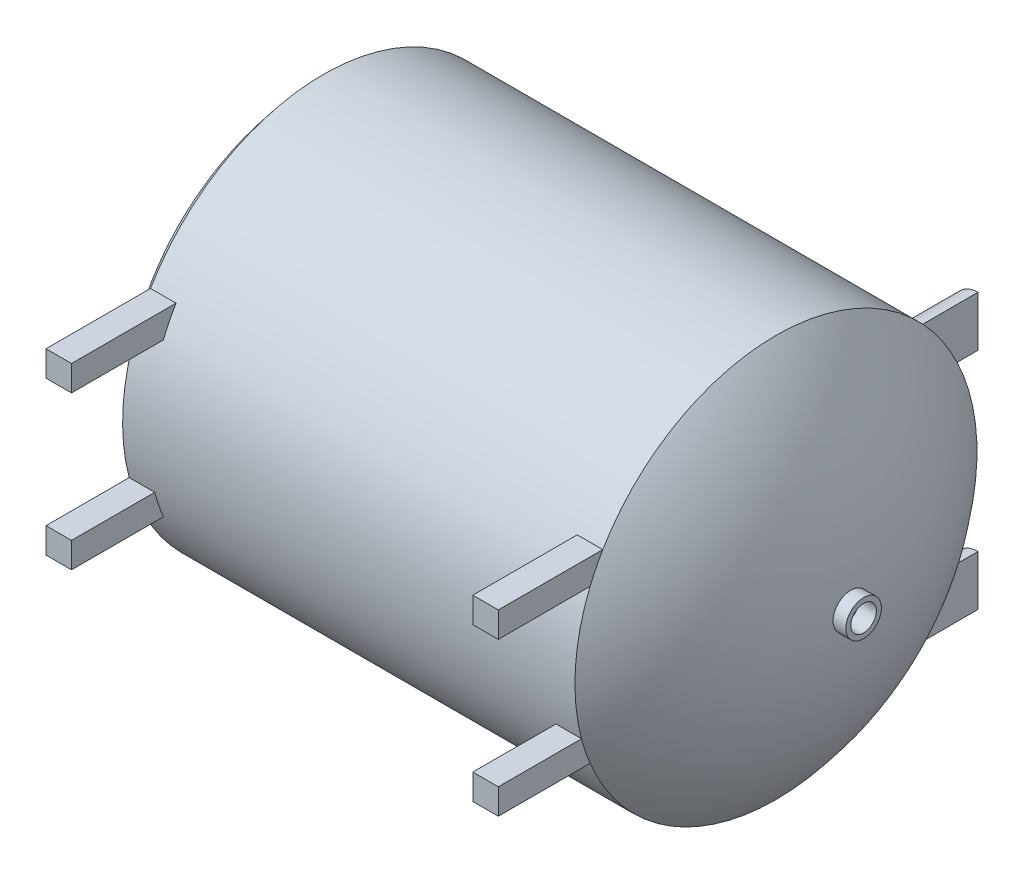
SolidWorks part; units mm, degrees
material "1060 Alloy"
ref_plane "Front" through (0, 0, 0) normal (0, 0, 1) x (1, 0, 0)
ref_plane "Top" through (0, 0, 0) normal (0, 1, 0) x (1, 0, 0)
ref_plane "Right" through (0, 0, 0) normal (1, 0, 0) x (0, 0, -1)
sketch "Sketch1" plane through (0, 0, 0) normal (0, 0, 1) x (1, 0, 0)
  line L0 (150, -400) -> (1050, -400)
  line L1 (600, -400) -> (600, 130.2021) construction
  line L2 (1198.9691, -35.4) -> (1224.3691, -35.4)
  line L3 (1224.3691, -35.4) -> (1224.3691, -25.4)
  line L4 (1224.3691, -25.4) -> (1199.4695, -25.4)
  line L5 (0, 0) -> (1200, 0) construction
  line L6 (154.5682, -390) -> (1045.4318, -390)
  line L7 (1199.4695, -25.4) -> (1189.4606, -25.4)
  line L8 (0, 0) -> (10, 0)
  arc A0 (0, 0) -> (150, -400) centre (608.3333, 0) ccw
  arc A1 (1198.9691, -35.4) -> (1050, -400) centre (591.6667, 0) cw
  arc A2 (1200, 0) -> (1199.4695, -25.4) centre (591.6667, 0) cw construction
  arc A3 (10, 0) -> (154.5682, -390) centre (608.3333, 0) ccw
  arc A4 (1189.4606, -25.4) -> (1045.4318, -390) centre (591.6667, 0) cw
  arc A6 (1189.4782, -24.9825) -> (1189.4606, -25.4) centre (591.6667, 0) cw construction
  arc A7 (1189.4782, -24.9825) -> (1045.4318, -390) centre (591.6667, 0) cw construction
  arc A8 (1199.4695, -25.4) -> (1198.9691, -35.4) centre (591.6667, 0) cw construction
  arc A9 (1199.4695, -25.4) -> (1050, -400) centre (591.6667, 0) cw construction
  dimension "D1" = 450
  dimension "D2" = 400
  dimension "D3" = 150
  dimension "D4" = 25.4
  dimension "D5" = 10
  dimension "D6" = 25.4
  dimension "D7" = 10
revolve "Revolve1" add sketch "Sketch1" angle 360 about L5
sketch "Sketch2" plane through (1224.3691, 0, 0) normal (1, 0, 0) x (0, 0, -1)
  line L0 (0, 0) -> (-25.4, 0) construction
  circle A0 centre (0, 0) radius 25.4 construction
ref_plane "Plane3" through (0, 0, -400) normal (0, 0, -1) x (-1, 0, 0)
ref_plane "Plane4" through (0, 0, -402) normal (0, 0, -1) x (-1, 0, 0)
sketch "Sketch4" plane through (0, 0, -402) normal (0, 0, -1) x (-1, 0, 0)
  line L0 (-1050, -400) -> (-1050, 400) construction
  line L1 (-1274.8214, 0) -> (-651.2379, 0) construction
  line L2 (-1050, 173.3121) -> (-1050, 273.3121)
  line L3 (-1050, 223.3121) -> (-864.1352, 223.3121) construction
  line L4 (-1050, -173.3121) -> (-1050, -273.3121)
  arc A0 (-1050, 173.3121) -> (-1050, 273.3121) centre (-1050, 223.3121) ccw
  arc A1 (-1050, -173.3121) -> (-1050, -273.3121) centre (-1050, -223.3121) cw
  dimension "D1" = 100
  dimension "D2" = 446.6241
extrude "Boss-Extrude1" add sketch "Sketch4" against normal up to surface (41.4963 mm away)
ref_plane "Plane8" through (0, 0, 400) normal (0, 0, 1) x (1, 0, 0)
ref_plane "Plane9" through (0, 0, 552.4) normal (0, 0, 1) x (1, 0, 0)
sketch "Sketch5" plane through (0, 0, 552.4) normal (0, 0, 1) x (1, 0, 0)
  line L0 (1050, -400) -> (1050, 400) construction
  line L1 (1050, 203.2) -> (999.2, 203.2)
  line L2 (1050, 203.2) -> (1050, 152.4)
  line L3 (1050, 152.4) -> (999.2, 152.4)
  line L4 (999.2, 203.2) -> (999.2, 152.4)
  line L5 (1050, 0) -> (573.9851, 0) construction
  line L6 (1050, 263.3826) -> (1050, -546.7025) construction
  line L7 (200.8, 203.2) -> (200.8, 152.4)
  line L8 (1050, -101.6) -> (999.2, -101.6)
  line L9 (1050, -101.6) -> (1050, -152.4)
  line L10 (1050, -152.4) -> (999.2, -152.4)
  line L11 (999.2, -101.6) -> (999.2, -152.4)
  line L12 (200.8, 203.2) -> (150, 203.2)
  line L13 (150, 203.2) -> (150, 152.4)
  line L14 (200.8, 152.4) -> (150, 152.4)
  line L15 (200.8, -101.6) -> (200.8, -152.4)
  line L16 (200.8, -101.6) -> (150, -101.6)
  line L17 (150, -101.6) -> (150, -152.4)
  line L18 (200.8, -152.4) -> (150, -152.4)
  dimension "D1" = 152.4
  dimension "D2" = 50.8
  dimension "D3" = 50.8
  dimension "D4" = 50.8
  dimension "D5" = 50.8
  dimension "D6" = 254
  dimension "D8" = 900
  dimension "D7" = 2
extrude "Boss-Extrude2" add sketch "Sketch5" against normal up to surface (207.8572 mm away)
